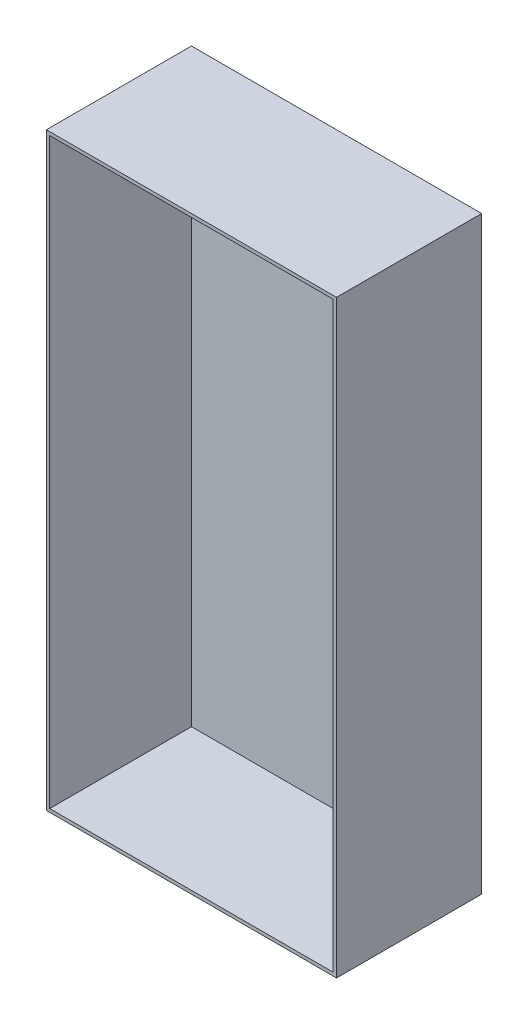
SolidWorks part; units mm, degrees
ref_plane "Front Plane" through (0, 0, 0) normal (1, 0, 0) x (0, 1, 0)
ref_plane "Top Plane" through (0, 0, 0) normal (0, 0, 1) x (0, 1, 0)
ref_plane "Right Plane" through (0, 0, 0) normal (0, 1, 0) x (-1, 0, 0)
sketch "Sketch1" plane through (0, 0, 0) normal (0, 0, 1) x (0, 1, 0)
  line L0 (0, -55) -> (0, 55) construction
  line L1 (-176.75, 50) -> (176.75, 50)
  line L2 (-176.75, 50) -> (-176.75, -124)
  line L3 (-176.75, -124) -> (176.75, -124)
  line L4 (176.75, 50) -> (176.75, -124)
  line L5 (-55, 0) -> (55, 0) construction
  dimension "WidthCar" = 174
  dimension "LengthCar" = 353.5
  dimension "L/2_Centering" = 176.75
  dimension "W/2_Centering" = 50
extrude "Boss-Extrude1" add sketch "Sketch1" along normal blind 87
shell "Shell1" thickness 2
equation "\"AA_Daimeter\"= 14.5"
equation "\"AA_Length\"= 50.5"
equation "\"H_Max\" = 100"
equation "\"W_Max\"= 200"
equation "\"L_Max\"= 350"
equation "\"L/2_Centering@Sketch1\"= \"LengthCar@Sketch1\" / 2"
equation "\"HeightCar@Boss-Extrude1\"= \"AA_Daimeter\" * 6"
equation "\"WidthCar@Sketch1\"= \"AA_Daimeter\" * 12"
equation "\"LengthCar@Sketch1\"= \"AA_Length\" * 7'Slightly Over"
